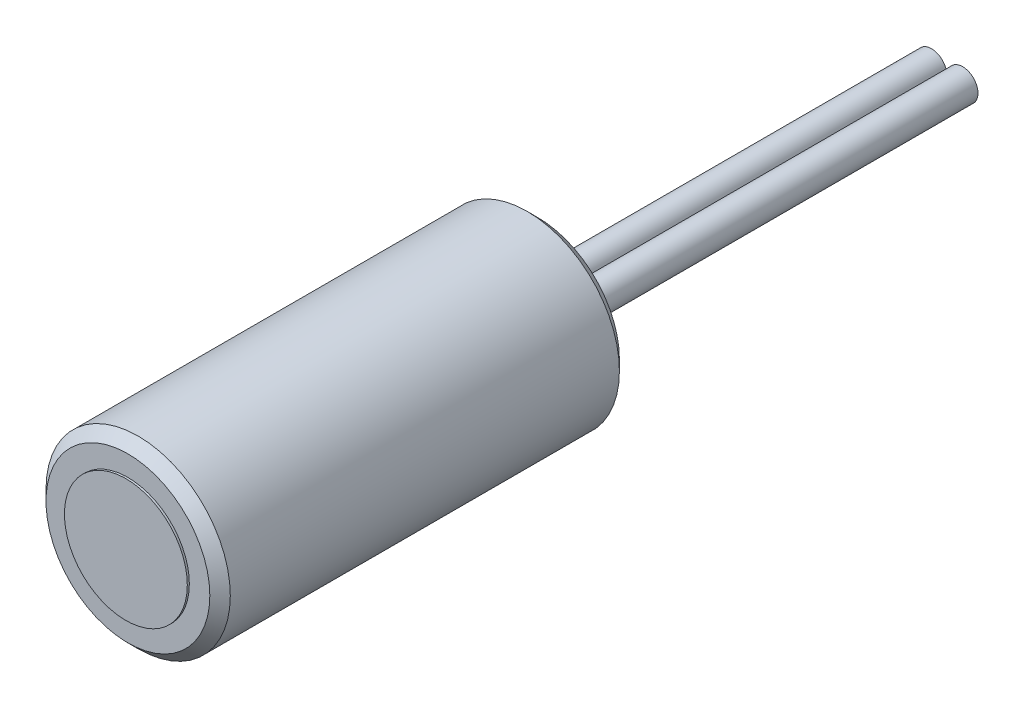
SolidWorks part; units mm, degrees
ref_plane "Face" through (0, 0, 0) normal (0, 0, 1) x (1, 0, 0)
ref_plane "Dessus" through (0, 0, 0) normal (0, 1, 0) x (1, 0, 0)
ref_plane "Droite" through (0, 0, 0) normal (1, 0, 0) x (0, 0, -1)
sketch "Esquisse2" plane through (0, 0, 0) normal (0, 0, 1) x (1, 0, 0)
  circle A0 centre (0, 0) radius 4.5
  dimension "D1" = 9
extrude "Boss.-Extru.1" add sketch "Esquisse2" along normal blind 20
chamfer "Chanfrein1" distance 0.5 angle 45 2 edges at (4.5, 0, 0) (4.5, 0, 20)
sketch "Esquisse3" plane through (0, 0, 20) normal (0, 0, 1) x (1, 0, 0)
  circle A0 centre (0, 0) radius 3
extrude "Boss.-Extru.4" add sketch "Esquisse3" along normal blind 0.1
sketch "Esquisse5" plane through (0, 0, 0) normal (0, 0, -1) x (-1, 0, 0)
  circle A0 centre (0.76, 0) radius 0.75
  circle A1 centre (-0.76, 0) radius 0.75
extrude "Boss.-Extru.5" add sketch "Esquisse5" along normal blind 20
